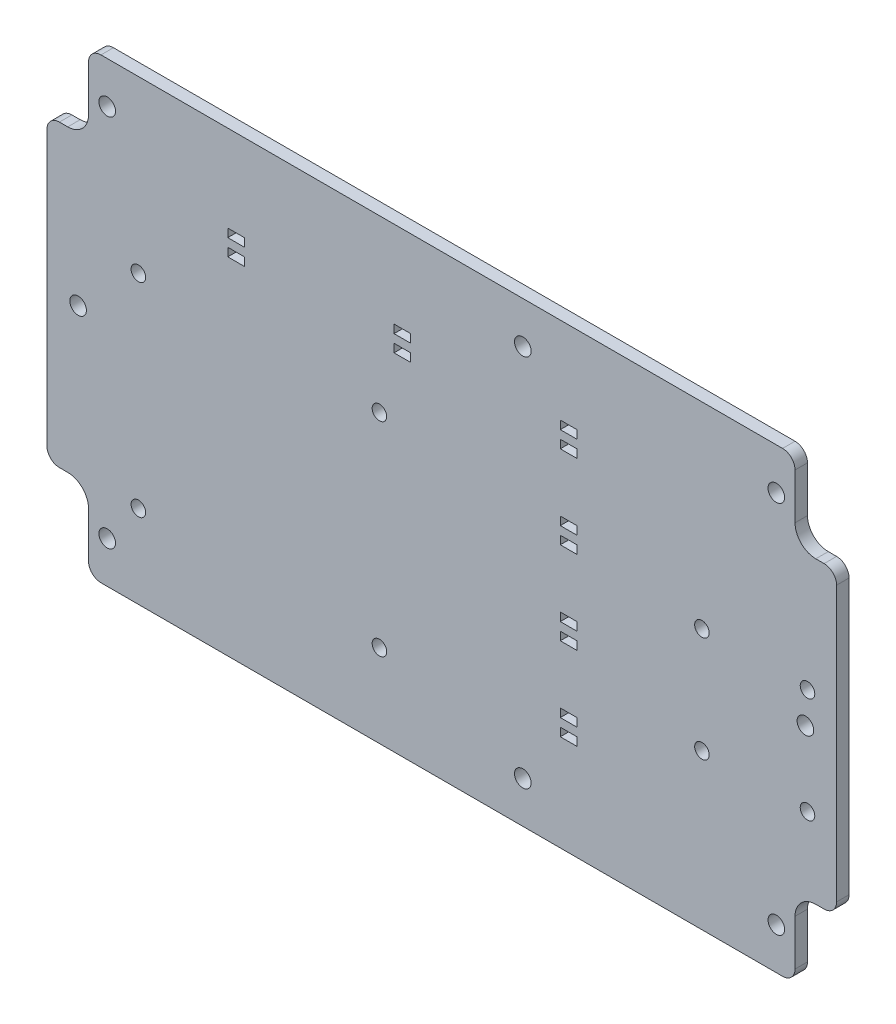
SolidWorks part; units mm, degrees
ref_plane "Front" through (0, 0, 0) normal (0, 0, 1) x (1, 0, 0)
ref_plane "Top" through (0, 0, 0) normal (0, 1, 0) x (1, 0, 0)
ref_plane "Right" through (0, 0, 0) normal (1, 0, 0) x (0, 0, -1)
sketch "Sketch1" plane through (0, 0, 0) normal (0, 0, 1) x (1, 0, 0)
  line L0 (-82, 55) -> (82, 55)
  line L1 (85, 52) -> (85, 41)
  line L2 (90, 36) -> (92, 36)
  line L3 (95, 33) -> (95, -33)
  line L4 (92, -36) -> (90, -36)
  line L5 (85, -41) -> (85, -52)
  line L6 (82, -55) -> (-82, -55)
  line L7 (-85, -52) -> (-85, -41)
  line L8 (-90, -36) -> (-92, -36)
  line L9 (-95, -33) -> (-95, 33)
  line L10 (-92, 36) -> (-90, 36)
  line L11 (-85, 41) -> (-85, 52)
  line L12 (-95, 0) -> (95, 0) construction
  line L13 (0, 55) -> (0, -55) construction
  line L14 (-85, 45) -> (85, 45) construction
  line L15 (-85, -45) -> (85, -45) construction
  line L16 (-80.5, 55) -> (-80.5, -55) construction
  line L17 (19.5, 55) -> (19.5, -55) construction
  line L18 (80.5, 55) -> (80.5, -55) construction
  circle A0 centre (-80.5, 45) radius 2
  circle A1 centre (19.5, 45) radius 2
  circle A2 centre (80.5, 45) radius 2
  circle A3 centre (-80.5, -45) radius 2
  circle A4 centre (-87.5, 0) radius 2
  circle A5 centre (87.5, 0) radius 2
  circle A6 centre (19.5, -45) radius 2
  circle A7 centre (80.5, -45) radius 2
  arc A8 (95, -33) -> (92, -36) centre (92, -33) cw
  arc A9 (92, 36) -> (95, 33) centre (92, 33) cw
  arc A10 (-92, -36) -> (-95, -33) centre (-92, -33) cw
  arc A11 (-95, 33) -> (-92, 36) centre (-92, 33) cw
  arc A12 (-82, -55) -> (-85, -52) centre (-82, -52) cw
  arc A13 (85, -52) -> (82, -55) centre (82, -52) cw
  arc A14 (82, 55) -> (85, 52) centre (82, 52) cw
  arc A15 (-82, 55) -> (-85, 52) centre (-82, 52) ccw
  arc A16 (85, 41) -> (90, 36) centre (90, 41) ccw
  arc A17 (90, -36) -> (85, -41) centre (90, -41) ccw
  arc A18 (-85, -41) -> (-90, -36) centre (-90, -41) ccw
  arc A19 (-90, 36) -> (-85, 41) centre (-90, 41) ccw
  point P23 (-91, -36)
  point P46 (95, -36)
  point P49 (95, 36)
  point P54 (-95, 36)
  point P57 (-85, -55)
  point P64 (-85, 55)
  point P69 (85, -36)
  point P72 (-85, -36)
  dimension "D9" = 4
  dimension "D10" = 3
  dimension "D11" = 3
  dimension "D12" = 3
  dimension "D13" = 5
  dimension "D1" = 190
  dimension "D2" = 110
  dimension "D3" = 170
  dimension "D4" = 72
  dimension "D5" = 90
  dimension "D6" = 100
  dimension "D7" = 61
  dimension "D8" = 175
extrude "Boss-Extrude1" add sketch "Sketch1" along normal blind 3
hole_wizard "Ø3.5 (3.5) Diameter Hole1" positions "Sketch2" profile "Sketch3" hole size "Ø3.5" standard "ANSI Metric" end condition up to next
sketch "Sketch2" plane through (0, 0, 3) normal (0, 0, 1) x (1, 0, 0)
  line L1 (62.6, 7.7) -> (88, 7.7) construction
  line L2 (62.6, 7.7) -> (62.6, -17.7) construction
  line L3 (62.6, -17.7) -> (88, -17.7) construction
  line L4 (88, 7.7) -> (88, -17.7) construction
  line L5 (95, -33) -> (95, 33) construction
  line L7 (-73, -35) -> (-15, -35) construction
  line L8 (-73, -35) -> (-73, 14) construction
  line L9 (-73, 14) -> (-15, 14) construction
  line L10 (-15, -35) -> (-15, 14) construction
  line L11 (-95, 33) -> (-95, -33) construction
  line L12 (-82, -55) -> (82, -55) construction
  point P0 (88, 7.7)
  point P2 (88, -17.7)
  point P4 (62.6, -17.7)
  point P6 (62.6, 7.7)
  point P86 (62.6, -5)
  point P94 (-73, 14)
  point P96 (-15, 14)
  point P98 (-15, -35)
  point P100 (-73, -35)
  point P156 (0, 0)
  point P157 (0, 0)
  point P158 (0, 0)
  point P159 (0, 0)
  dimension "D1" = 5
  dimension "D2" = 25.4
  dimension "D3" = 25.4
  dimension "D4" = 7
  dimension "D5" = 58
  dimension "D6" = 49
  dimension "D7" = 22
  dimension "D8" = 20
sketch "Sketch3" plane through (88, 7.7, 3) normal (1, 0, 0) x (0, -1, 0)
  line L0 (0, 0) -> (0, 3)
  line L1 (0, 3) -> (1.75, 3)
  line L2 (1.75, 3) -> (1.75, 0)
  line L5 (1.75, 0) -> (0, 0)
  line L11 (0, -6.35) -> (0, 107.95) construction
  dimension "Thru Hole Dia." = 3.5
  dimension "Thru Hole Depth" = 3
sketch "Sketch4" plane through (0, 0, 3) normal (0, 0, 1) x (1, 0, 0)
  line L0 (-11.4828, 34.1753) -> (-7.4828, 34.1753)
  line L1 (-51.4828, 34.1753) -> (-47.4828, 34.1753)
  line L2 (-51.4828, 34.1753) -> (-51.4828, 32.1753)
  line L3 (-51.4828, 32.1753) -> (-47.4828, 32.1753)
  line L4 (-47.4828, 34.1753) -> (-47.4828, 32.1753)
  line L5 (-51.4828, 30.1753) -> (-47.4828, 30.1753)
  line L6 (-51.4828, 30.1753) -> (-51.4828, 28.1753)
  line L7 (-51.4828, 28.1753) -> (-47.4828, 28.1753)
  line L8 (-47.4828, 30.1753) -> (-47.4828, 28.1753)
  line L9 (-11.4828, 34.1753) -> (-11.4828, 32.1753)
  line L10 (-11.4828, 32.1753) -> (-7.4828, 32.1753)
  line L11 (-7.4828, 34.1753) -> (-7.4828, 32.1753)
  line L12 (-11.4828, 30.1753) -> (-7.4828, 30.1753)
  line L13 (-11.4828, 30.1753) -> (-11.4828, 28.1753)
  line L14 (-11.4828, 28.1753) -> (-7.4828, 28.1753)
  line L15 (-7.4828, 30.1753) -> (-7.4828, 28.1753)
  line L16 (28.5172, 34.1753) -> (32.5172, 34.1753)
  line L17 (28.5172, 34.1753) -> (28.5172, 32.1753)
  line L18 (28.5172, 32.1753) -> (32.5172, 32.1753)
  line L19 (32.5172, 34.1753) -> (32.5172, 32.1753)
  line L20 (28.5172, 30.1753) -> (32.5172, 30.1753)
  line L21 (28.5172, 30.1753) -> (28.5172, 28.1753)
  line L22 (28.5172, 28.1753) -> (32.5172, 28.1753)
  line L23 (32.5172, 30.1753) -> (32.5172, 28.1753)
  line L24 (68.5172, 34.1753) -> (72.5172, 34.1753) [skipped]
  line L25 (68.5172, 34.1753) -> (68.5172, 32.1753) [skipped]
  line L26 (68.5172, 32.1753) -> (72.5172, 32.1753) [skipped]
  line L27 (72.5172, 34.1753) -> (72.5172, 32.1753) [skipped]
  line L28 (68.5172, 30.1753) -> (72.5172, 30.1753) [skipped]
  line L29 (68.5172, 30.1753) -> (68.5172, 28.1753) [skipped]
  line L30 (68.5172, 28.1753) -> (72.5172, 28.1753) [skipped]
  line L31 (72.5172, 30.1753) -> (72.5172, 28.1753) [skipped]
  line L32 (-11.4828, 14.1753) -> (-7.4828, 14.1753) [skipped]
  line L33 (-11.4828, 14.1753) -> (-11.4828, 12.1753) [skipped]
  line L34 (-11.4828, 12.1753) -> (-7.4828, 12.1753) [skipped]
  line L35 (-7.4828, 14.1753) -> (-7.4828, 12.1753) [skipped]
  line L36 (-11.4828, 10.1753) -> (-7.4828, 10.1753) [skipped]
  line L37 (-11.4828, 10.1753) -> (-11.4828, 8.1753) [skipped]
  line L38 (-11.4828, 8.1753) -> (-7.4828, 8.1753) [skipped]
  line L39 (-7.4828, 10.1753) -> (-7.4828, 8.1753) [skipped]
  line L40 (28.5172, 14.1753) -> (32.5172, 14.1753)
  line L41 (28.5172, 14.1753) -> (28.5172, 12.1753)
  line L42 (28.5172, 12.1753) -> (32.5172, 12.1753)
  line L43 (32.5172, 14.1753) -> (32.5172, 12.1753)
  line L44 (28.5172, 10.1753) -> (32.5172, 10.1753)
  line L45 (28.5172, 10.1753) -> (28.5172, 8.1753)
  line L46 (28.5172, 8.1753) -> (32.5172, 8.1753)
  line L47 (32.5172, 10.1753) -> (32.5172, 8.1753)
  line L48 (68.5172, 14.1753) -> (72.5172, 14.1753) [skipped]
  line L49 (68.5172, 14.1753) -> (68.5172, 12.1753) [skipped]
  line L50 (68.5172, 12.1753) -> (72.5172, 12.1753) [skipped]
  line L51 (72.5172, 14.1753) -> (72.5172, 12.1753) [skipped]
  line L52 (68.5172, 10.1753) -> (72.5172, 10.1753) [skipped]
  line L53 (68.5172, 10.1753) -> (68.5172, 8.1753) [skipped]
  line L54 (68.5172, 8.1753) -> (72.5172, 8.1753) [skipped]
  line L55 (72.5172, 10.1753) -> (72.5172, 8.1753) [skipped]
  line L56 (-11.4828, -5.8247) -> (-7.4828, -5.8247) [skipped]
  line L57 (-11.4828, -5.8247) -> (-11.4828, -7.8247) [skipped]
  line L58 (-11.4828, -7.8247) -> (-7.4828, -7.8247) [skipped]
  line L59 (-7.4828, -5.8247) -> (-7.4828, -7.8247) [skipped]
  line L60 (-11.4828, -9.8247) -> (-7.4828, -9.8247) [skipped]
  line L61 (-11.4828, -9.8247) -> (-11.4828, -11.8247) [skipped]
  line L62 (-11.4828, -11.8247) -> (-7.4828, -11.8247) [skipped]
  line L63 (-7.4828, -9.8247) -> (-7.4828, -11.8247) [skipped]
  line L64 (28.5172, -5.8247) -> (32.5172, -5.8247)
  line L65 (28.5172, -5.8247) -> (28.5172, -7.8247)
  line L66 (28.5172, -7.8247) -> (32.5172, -7.8247)
  line L67 (32.5172, -5.8247) -> (32.5172, -7.8247)
  line L68 (28.5172, -9.8247) -> (32.5172, -9.8247)
  line L69 (28.5172, -9.8247) -> (28.5172, -11.8247)
  line L70 (28.5172, -11.8247) -> (32.5172, -11.8247)
  line L71 (32.5172, -9.8247) -> (32.5172, -11.8247)
  line L72 (68.5172, -5.8247) -> (72.5172, -5.8247) [skipped]
  line L73 (68.5172, -5.8247) -> (68.5172, -7.8247) [skipped]
  line L74 (68.5172, -7.8247) -> (72.5172, -7.8247) [skipped]
  line L75 (72.5172, -5.8247) -> (72.5172, -7.8247) [skipped]
  line L76 (68.5172, -9.8247) -> (72.5172, -9.8247) [skipped]
  line L77 (68.5172, -9.8247) -> (68.5172, -11.8247) [skipped]
  line L78 (68.5172, -11.8247) -> (72.5172, -11.8247) [skipped]
  line L79 (72.5172, -9.8247) -> (72.5172, -11.8247) [skipped]
  line L80 (-11.4828, -25.8247) -> (-7.4828, -25.8247) [skipped]
  line L81 (-11.4828, -25.8247) -> (-11.4828, -27.8247) [skipped]
  line L82 (-11.4828, -27.8247) -> (-7.4828, -27.8247) [skipped]
  line L83 (-7.4828, -25.8247) -> (-7.4828, -27.8247) [skipped]
  line L84 (-11.4828, -29.8247) -> (-7.4828, -29.8247) [skipped]
  line L85 (-11.4828, -29.8247) -> (-11.4828, -31.8247) [skipped]
  line L86 (-11.4828, -31.8247) -> (-7.4828, -31.8247) [skipped]
  line L87 (-7.4828, -29.8247) -> (-7.4828, -31.8247) [skipped]
  line L88 (28.5172, -25.8247) -> (32.5172, -25.8247)
  line L89 (28.5172, -25.8247) -> (28.5172, -27.8247)
  line L90 (28.5172, -27.8247) -> (32.5172, -27.8247)
  line L91 (32.5172, -25.8247) -> (32.5172, -27.8247)
  line L92 (28.5172, -29.8247) -> (32.5172, -29.8247)
  line L93 (28.5172, -29.8247) -> (28.5172, -31.8247)
  line L94 (28.5172, -31.8247) -> (32.5172, -31.8247)
  line L95 (32.5172, -29.8247) -> (32.5172, -31.8247)
  line L96 (68.5172, -25.8247) -> (72.5172, -25.8247) [skipped]
  line L97 (68.5172, -25.8247) -> (68.5172, -27.8247) [skipped]
  line L98 (68.5172, -27.8247) -> (72.5172, -27.8247) [skipped]
  line L99 (72.5172, -25.8247) -> (72.5172, -27.8247) [skipped]
  line L100 (68.5172, -29.8247) -> (72.5172, -29.8247) [skipped]
  line L101 (68.5172, -29.8247) -> (68.5172, -31.8247) [skipped]
  line L102 (68.5172, -31.8247) -> (72.5172, -31.8247) [skipped]
  line L103 (72.5172, -29.8247) -> (72.5172, -31.8247) [skipped]
  line L104 (-51.4828, 14.1753) -> (-47.4828, 14.1753) [skipped]
  line L105 (-51.4828, 14.1753) -> (-51.4828, 12.1753) [skipped]
  line L106 (-51.4828, 12.1753) -> (-47.4828, 12.1753) [skipped]
  line L107 (-47.4828, 14.1753) -> (-47.4828, 12.1753) [skipped]
  line L108 (-51.4828, 10.1753) -> (-47.4828, 10.1753) [skipped]
  line L109 (-51.4828, 10.1753) -> (-51.4828, 8.1753) [skipped]
  line L110 (-51.4828, 8.1753) -> (-47.4828, 8.1753) [skipped]
  line L111 (-47.4828, 10.1753) -> (-47.4828, 8.1753) [skipped]
  line L112 (-51.4828, -5.8247) -> (-47.4828, -5.8247) [skipped]
  line L113 (-51.4828, -5.8247) -> (-51.4828, -7.8247) [skipped]
  line L114 (-51.4828, -7.8247) -> (-47.4828, -7.8247) [skipped]
  line L115 (-47.4828, -5.8247) -> (-47.4828, -7.8247) [skipped]
  line L116 (-51.4828, -9.8247) -> (-47.4828, -9.8247) [skipped]
  line L117 (-51.4828, -9.8247) -> (-51.4828, -11.8247) [skipped]
  line L118 (-51.4828, -11.8247) -> (-47.4828, -11.8247) [skipped]
  line L119 (-47.4828, -9.8247) -> (-47.4828, -11.8247) [skipped]
  line L120 (-51.4828, -25.8247) -> (-47.4828, -25.8247) [skipped]
  line L121 (-51.4828, -25.8247) -> (-51.4828, -27.8247) [skipped]
  line L122 (-51.4828, -27.8247) -> (-47.4828, -27.8247) [skipped]
  line L123 (-47.4828, -25.8247) -> (-47.4828, -27.8247) [skipped]
  line L124 (-51.4828, -29.8247) -> (-47.4828, -29.8247) [skipped]
  line L125 (-51.4828, -29.8247) -> (-51.4828, -31.8247) [skipped]
  line L126 (-51.4828, -31.8247) -> (-47.4828, -31.8247) [skipped]
  line L127 (-47.4828, -29.8247) -> (-47.4828, -31.8247) [skipped]
  dimension "D1" = 2
  dimension "D2" = 2
  dimension "D3" = 2
  dimension "D4" = 4
  dimension "D5" = 4
  dimension "D6" = 4
  dimension "D7" = 4
extrude "Cut-Extrude1" cut sketch "Sketch4" against normal through all
